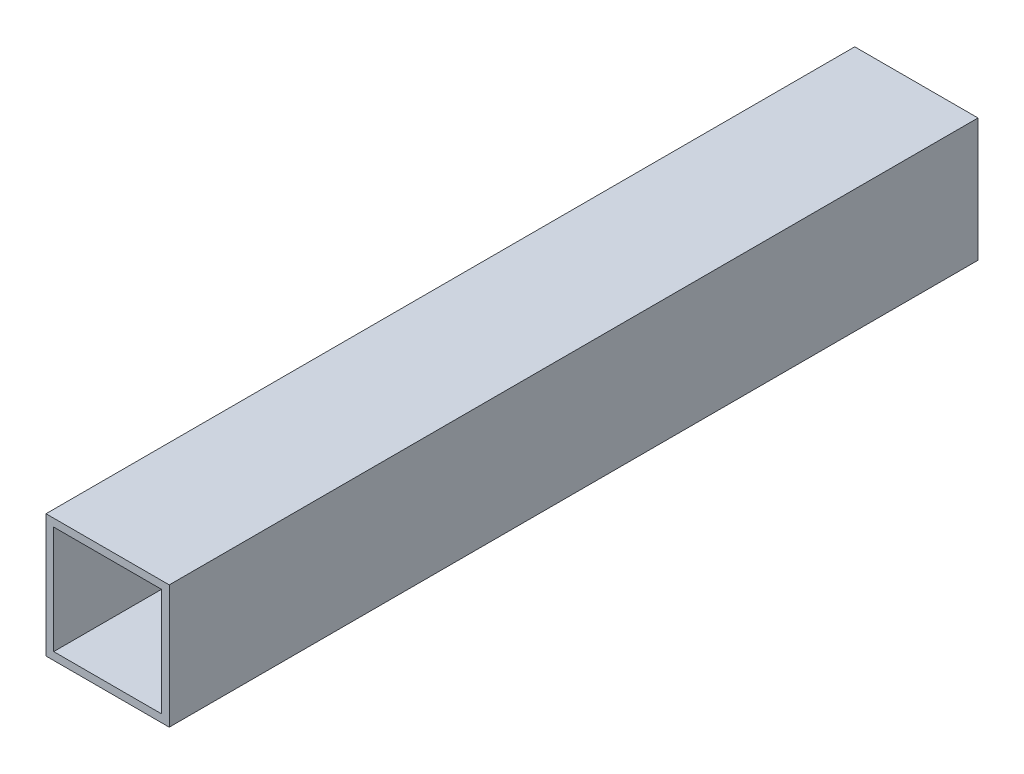
SolidWorks part; units mm, degrees
ref_plane "Alzado" through (0, 0, 0) normal (0, 0, 1) x (1, 0, 0)
ref_plane "Planta" through (0, 0, 0) normal (0, 1, 0) x (1, 0, 0)
ref_plane "Vista lateral" through (0, 0, 0) normal (1, 0, 0) x (0, 0, -1)
sketch "Croquis1" plane through (0, 0, 0) normal (0, 0, 1) x (1, 0, 0)
  line L0 (4.7625, -4.7625) -> (71.4375, -4.7625)
  line L1 (0, 0) -> (76.2, 0)
  line L2 (0, 0) -> (0, -76.2)
  line L3 (0, -76.2) -> (76.2, -76.2)
  line L4 (76.2, 0) -> (76.2, -76.2)
  line L5 (71.4375, -4.7625) -> (71.4375, -71.4375)
  line L6 (4.7625, -71.4375) -> (71.4375, -71.4375)
  line L7 (4.7625, -4.7625) -> (4.7625, -71.4375)
  dimension "D1" = 76.2
  dimension "D2" = 76.2
  dimension "D3" = 4.7625
extrude "Saliente-Extruir1" add sketch "Croquis1" along normal blind 500
